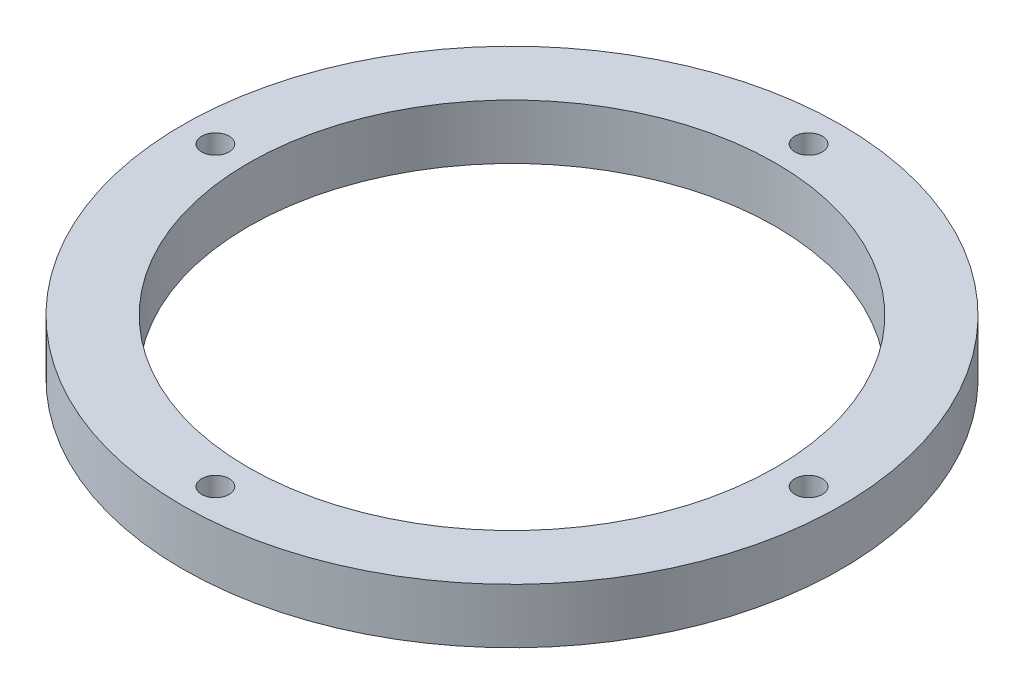
SolidWorks part; units mm, degrees
material "1060 Alloy"
ref_plane "Frontal Plane" through (0, 0, 0) normal (0, 0, 1) x (1, 0, 0)
ref_plane "Horizontal Plane" through (0, 0, 0) normal (0, 1, 0) x (1, 0, 0)
ref_plane "Profile Plane" through (0, 0, 0) normal (1, 0, 0) x (0, 0, -1)
sketch "Sketch1" plane through (0, 0, 0) normal (0, 1, 0) x (1, 0, 0)
  line L0 (0, 0) -> (-54, 0) construction
  circle A0 centre (0, 0) radius 48
  circle A1 centre (0, 0) radius 60
  circle A2 centre (-54, 0) radius 2.5
  circle A3 centre (0, 54) radius 2.5
  circle A4 centre (54, 0) radius 2.5
  circle A5 centre (0, -54) radius 2.5
  dimension "D1" = 120
  dimension "D3" = 5
  dimension "D2" = 12
  dimension "D4" = 54
  dimension "D5" = 4
extrude "Boss-Extrude1" add sketch "Sketch1" along normal blind 10
equation "\"PinDiameter\"= 0"
equation "\"WallThickness\"= 0.5cm"
equation "\"BottomPlateX\"= 3ft"
equation "\"ActuatorL\"= 35cm"
equation "\"ActuatorPinD\"= 6.35mm"
equation "\"ActuatorPinL\"= 15cm"
equation "\"Box-X\"= 40cm"
equation "\"Box-Z\"= 20cm"
equation "\"Box-Y\"= 30cm"
equation "\"ArmPlateThickness\"= .125in"
equation "\"ArmPlateX\"= 18in"
equation "\"ArmPlateDepth\"= 7.1875in"
equation "\"Arm1X\"= 5cm"
equation "\"Arm1L\"= 60cm"
equation "\"Arm2GAP\"= 5cm"
equation "\"Arm2L\"= 60cm"
equation "\"Arm2H\"= 5cm"
equation "\"Arm2Extension\"= 5cm"
equation "\"Arm3GAP\"= 5cm"
equation "\"Arm3L\"= 60cm"
equation "\"Arm3H\"= 5cm"
equation "\"Pin1-2L\"= \"Arm2GAP\" + (2 * \"WallThickness\")"
equation "\"Pin2-3L\"= \"Arm3GAP\" + (4 * \"WallThickness\")"
equation "\"DCMotor1D\"= 65mm"
equation "\"DCMotor1L\"= 215mm"
equation "\"DCMotor1ShaftL\"= 30mm"
equation "\"DCMotor2X\"= 68mm"
equation "\"DCMotor2D\"= 65mm"
equation "\"DCMotor2L\"= 208mm"
equation "\"DCMotor2ShaftL\"= 39mm"
equation "\"DCMotor2ShaftD\"= 15mm"
equation "\"BenchDepth\"= 5cm"
equation "\"BenchH\"= 10cm"
equation "\"BenchL\"= 15cm"
equation "\"PillowBlockW\"= 5cm"
equation "\"PillowBlockCenterH\"= \"DCMotor2X\"/2"
equation "\"EncoderRadius\"= 19mm"
equation "\"EncoderShaftL\"= 15mm"
equation "\"EncoderL\"= 33mm"
equation "\"EncoderHousingThickness\"= 7.5mm"
equation "\"TurntableID\"= 70mm"
equation "\"TurntableOD\"= 120mm"
equation "\"D1@Sketch1\"=\"TurntableOD\""
equation "\"D2@Sketch1\"=(\"TurntableOD\"-\"TurntableID\")*.25-.5mm"
equation "\"D4@Sketch1\"=\"TurntableOuterHoleRadius\""
equation "\"BottomPlateZ\"= 2ft"
equation "\"BottomPlateHoleD\"=((\"ArmPlateX\")^2+(\"ArmPlateDepth\")^2)^.5+ 10mm"
equation "\"TurntableInner2*t\" = (\"TurntableOD\"-\"TurntableID\")*.25 - 1mm"
equation "\"TurntableInnerHoleRadius\"= \"TurntableID\"*.5 + \"TurntableInner2*t\"*.5"
equation "\"TurntableOuterHoleRadius\" = \"TurntableOD\"*.5 - ((\"TurntableOD\"-\"TurntableID\")*.25-.5mm)*.5"
equation "\"RotaryUnionThickness\"= 1cm"
